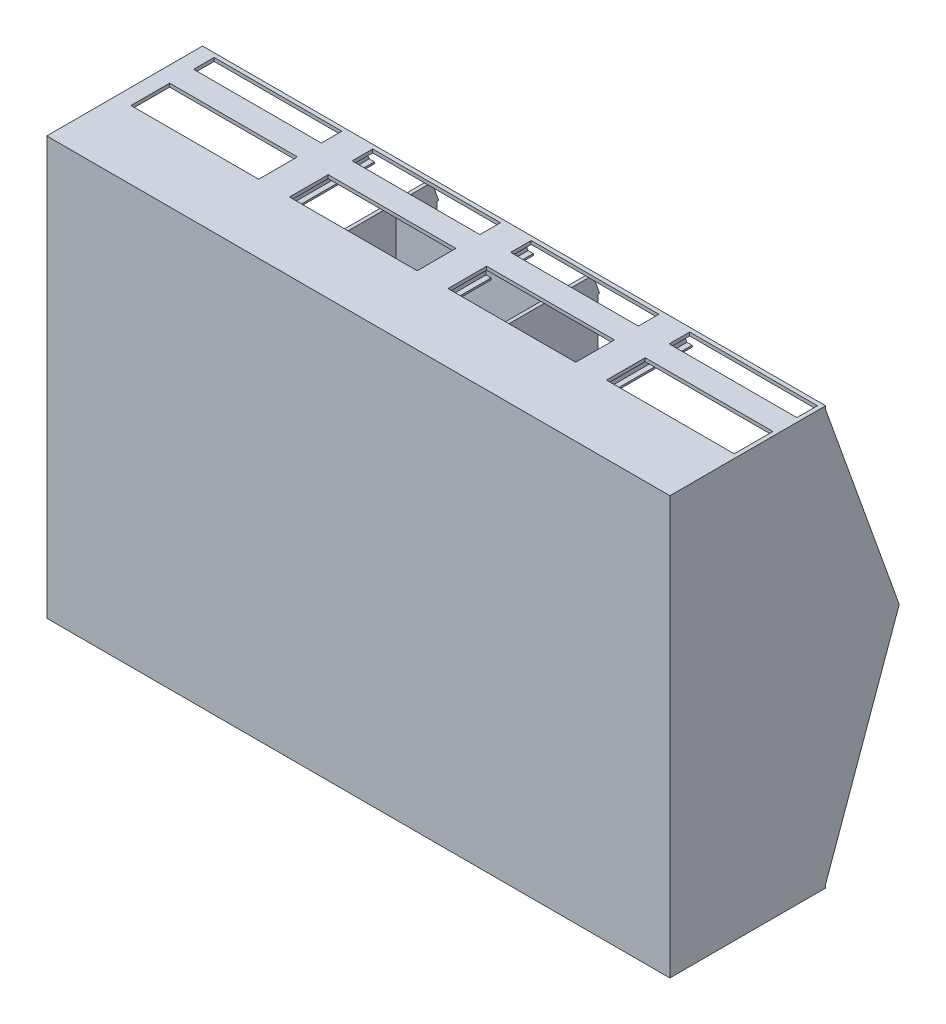
SolidWorks part; units mm, degrees
ref_plane "正面" through (0, 0, 0) normal (0, 0, 1) x (1, 0, 0)
ref_plane "平面" through (0, 0, 0) normal (0, 1, 0) x (1, 0, 0)
ref_plane "右側面" through (0, 0, 0) normal (1, 0, 0) x (0, 0, -1)
sketch "ｽｹｯﾁ1" plane through (0, 0, 0) normal (0, 0, 1) x (1, 0, 0)
  line L1 (-67.545, 11958.8232) -> (18032.455, 11958.8232)
  line L2 (-67.545, 11958.8232) -> (-67.545, -41.1768)
  line L3 (-67.545, -41.1768) -> (18032.455, -41.1768)
  line L4 (18032.455, 11958.8232) -> (18032.455, -41.1768)
  dimension "D1" = 18100
  dimension "D2" = 12000
extrude "ﾎﾞｽ - 押し出し1" add sketch "ｽｹｯﾁ1" along normal blind 1000
sketch "ｽｹｯﾁ11" plane through (18032.455, 0, 0) normal (1, 0, 0) x (0, 0, -1)
  line L1 (-1000, 11958.8232) -> (5700, 11958.8232)
  line L2 (-1000, 11958.8232) -> (-1000, -41.1768)
  line L3 (-1000, -41.1768) -> (5700, -41.1768)
  line L4 (5700, 11958.8232) -> (5700, -41.1768)
  dimension "D1" = 12000
  dimension "D2" = 6700
extrude "ﾎﾞｽ - 押し出し7" add sketch "ｽｹｯﾁ11" along normal blind 100
sketch "ｽｹｯﾁ12" plane through (0, -41.1768, 0) normal (0, -1, 0) x (-1, 0, 0)
  line L0 (67.545, -1000) -> (67.545, 0) construction
  line L1 (-18132.455, -1000) -> (67.545, -1000)
  line L2 (-18132.455, -1000) -> (-18132.455, 3550)
  line L3 (-18132.455, 3550) -> (67.545, 3550)
  line L4 (67.545, -1000) -> (67.545, 3550)
  dimension "D1" = 4550
extrude "ﾎﾞｽ - 押し出し8" add sketch "ｽｹｯﾁ12" along normal blind 100
sketch "ｽｹｯﾁ13" plane through (0, 11958.8232, 0) normal (0, 1, 0) x (1, 0, 0)
  line L1 (18132.455, -1000) -> (-67.545, -1000)
  line L2 (18132.455, -1000) -> (18132.455, 3550)
  line L3 (18132.455, 3550) -> (-67.545, 3550)
  line L4 (-67.545, -1000) -> (-67.545, 3550)
  line L5 (-67.545, 0) -> (-67.545, 3550) construction
  dimension "D1" = 0
  dimension "D2" = 4550
extrude "ﾎﾞｽ - 押し出し9" add sketch "ｽｹｯﾁ13" along normal blind 100
sketch "ｽｹｯﾁ14" plane through (0, 0, 0) normal (0, 0, -1) x (-1, 0, 0)
  line L0 (67.545, -41.1768) -> (-18032.455, -41.1768) construction
  line L1 (-6532.455, -41.1768) -> (-6632.455, -41.1768)
  line L2 (-6532.455, -41.1768) -> (-6532.455, 11958.8232)
  line L3 (-6532.455, 11958.8232) -> (-6632.455, 11958.8232)
  line L4 (-6632.455, -41.1768) -> (-6632.455, 11958.8232)
  line L5 (-18032.455, 11958.8232) -> (67.545, 11958.8232) construction
  line L6 (67.545, -41.1768) -> (-18032.455, -41.1768) construction
  line L7 (-11232.455, -41.1768) -> (-11332.455, -41.1768)
  line L8 (-11232.455, -41.1768) -> (-11232.455, 11958.8232)
  line L9 (-11232.455, 11958.8232) -> (-11332.455, 11958.8232)
  line L10 (-11332.455, -41.1768) -> (-11332.455, 11958.8232)
  line L11 (-18032.455, 11958.8232) -> (67.545, 11958.8232) construction
  line L12 (67.545, 11958.8232) -> (67.545, -41.1768) construction
  dimension "D1" = 100
  dimension "D2" = 100
  dimension "D3" = 4600
  dimension "D4" = 6600
extrude "ﾎﾞｽ - 押し出し10" add sketch "ｽｹｯﾁ14" along normal blind 5700
sketch "ｽｹｯﾁ16" plane through (0, 0, 0) normal (0, 0, -1) x (-1, 0, 0)
  line L0 (67.545, -41.1768) -> (-6532.455, -41.1768) construction
  line L1 (-4622.455, -41.1768) -> (-4522.455, -41.1768)
  line L2 (-4622.455, -41.1768) -> (-4622.455, 458.8232)
  line L3 (-4522.455, 458.8232) -> (-4372.455, 458.8232)
  line L4 (-4522.455, -41.1768) -> (-4522.455, 458.8232)
  line L5 (-6632.455, -41.1768) -> (-11232.455, -41.1768) construction
  line L6 (-4772.455, 508.8232) -> (-4372.455, 508.8232)
  line L7 (-4772.455, 508.8232) -> (-4772.455, 458.8232)
  line L8 (-4772.455, 458.8232) -> (-4622.455, 458.8232)
  line L9 (-4372.455, 508.8232) -> (-4372.455, 458.8232)
  line L10 (-9262.455, -41.1768) -> (-9162.455, -41.1768)
  line L11 (-9262.455, -41.1768) -> (-9262.455, 458.8232)
  line L12 (-9162.455, 458.8232) -> (-9012.455, 458.8232)
  line L13 (-9162.455, -41.1768) -> (-9162.455, 458.8232)
  line L14 (-11332.455, -41.1768) -> (-18032.455, -41.1768) construction
  line L15 (-9412.455, 508.8232) -> (-9012.455, 508.8232)
  line L16 (-9412.455, 508.8232) -> (-9412.455, 458.8232)
  line L17 (-9412.455, 458.8232) -> (-9262.455, 458.8232)
  line L18 (-9012.455, 508.8232) -> (-9012.455, 458.8232)
  line L19 (-13902.455, -41.1768) -> (-13802.455, -41.1768)
  line L20 (-13902.455, -41.1768) -> (-13902.455, 458.8232)
  line L21 (-13802.455, 458.8232) -> (-13652.455, 458.8232)
  line L22 (-13802.455, -41.1768) -> (-13802.455, 458.8232)
  line L23 (-18032.455, 11958.8232) -> (-11332.455, 11958.8232) construction
  line L24 (-14052.455, 508.8232) -> (-13652.455, 508.8232)
  line L25 (-14052.455, 508.8232) -> (-14052.455, 458.8232)
  line L26 (-14052.455, 458.8232) -> (-13902.455, 458.8232)
  line L27 (-13652.455, 508.8232) -> (-13652.455, 458.8232)
  line L28 (-13902.455, 11958.8232) -> (-13802.455, 11958.8232)
  line L29 (-13902.455, 11958.8232) -> (-13902.455, 11458.8232)
  line L30 (-13802.455, 11458.8232) -> (-13652.455, 11458.8232)
  line L31 (-13802.455, 11958.8232) -> (-13802.455, 11458.8232)
  line L32 (-11232.455, 11958.8232) -> (-6632.455, 11958.8232) construction
  line L33 (-14052.455, 11458.8232) -> (-13902.455, 11458.8232)
  line L34 (-14052.455, 11458.8232) -> (-14052.455, 11408.8232)
  line L35 (-14052.455, 11408.8232) -> (-13652.455, 11408.8232)
  line L36 (-13652.455, 11458.8232) -> (-13652.455, 11408.8232)
  line L37 (-9262.455, 11958.8232) -> (-9162.455, 11958.8232)
  line L38 (-9262.455, 11958.8232) -> (-9262.455, 11458.8232)
  line L39 (-9162.455, 11458.8232) -> (-9012.455, 11458.8232)
  line L40 (-9162.455, 11958.8232) -> (-9162.455, 11458.8232)
  line L41 (-6532.455, 11958.8232) -> (67.545, 11958.8232) construction
  line L42 (-9412.455, 11408.8232) -> (-9012.455, 11408.8232)
  line L43 (-9412.455, 11408.8232) -> (-9412.455, 11458.8232)
  line L44 (-9412.455, 11458.8232) -> (-9262.455, 11458.8232)
  line L45 (-9012.455, 11408.8232) -> (-9012.455, 11458.8232)
  line L46 (-4622.455, 11958.8232) -> (-4522.455, 11958.8232)
  line L47 (-4622.455, 11958.8232) -> (-4622.455, 11458.8232)
  line L48 (-4522.455, 11458.8232) -> (-4372.455, 11458.8232)
  line L49 (-4522.455, 11958.8232) -> (-4522.455, 11458.8232)
  line L50 (-13852.455, 13375.4097) -> (-13852.455, -2224.1741) construction
  line L51 (-4772.455, 11408.8232) -> (-4372.455, 11408.8232)
  line L52 (-4772.455, 11408.8232) -> (-4772.455, 11458.8232)
  line L53 (-4772.455, 11458.8232) -> (-4622.455, 11458.8232)
  line L54 (-4372.455, 11408.8232) -> (-4372.455, 11458.8232)
  line L55 (-9212.455, 16545.7899) -> (-9212.455, -4246.1418) construction
  line L56 (-4572.455, 15782.7832) -> (-4572.455, -2796.4291) construction
  line L57 (67.545, 11958.8232) -> (67.545, -41.1768) construction
  dimension "D1" = 400
  dimension "D2" = 150
  dimension "D3" = 100
  dimension "D4" = 50
  dimension "D5" = 500
  dimension "D6" = 400
  dimension "D7" = 50
  dimension "D8" = 150
  dimension "D9" = 100
  dimension "D10" = 500
  dimension "D11" = 50
  dimension "D12" = 100
  dimension "D13" = 400
  dimension "D14" = 150
  dimension "D15" = 500
  dimension "D16" = 400
  dimension "D17" = 150
  dimension "D18" = 100
  dimension "D19" = 50
  dimension "D20" = 500
  dimension "D21" = 500
  dimension "D22" = 50
  dimension "D23" = 400
  dimension "D24" = 100
  dimension "D25" = 150
  dimension "D26" = 400
  dimension "D27" = 50
  dimension "D28" = 500
  dimension "D29" = 150
  dimension "D30" = 100
  dimension "D31" = 50
  dimension "D32" = 50
  dimension "D33" = 50
  dimension "D34" = 50
  dimension "D35" = 50
  dimension "D36" = 50
  dimension "D37" = 4640
  dimension "D38" = 4640
  dimension "D39" = 4640
extrude "ﾎﾞｽ - 押し出し11" add sketch "ｽｹｯﾁ16" along normal blind 5000
sketch "ｽｹｯﾁ15" plane through (18132.455, 0, 0) normal (1, 0, 0) x (0, 0, -1)
  line L0 (5700, 11958.8232) -> (3550, 11958.8232)
  line L1 (3550, 11958.8232) -> (5700, 5958.8232)
  line L2 (5700, -41.1768) -> (5700, 11958.8232) construction
  line L3 (5700, 5958.8232) -> (3550, -41.1768)
  line L4 (3550, -41.1768) -> (5700, -41.1768)
  line L5 (5700, -41.1768) -> (5700, 11958.8232)
  line L6 (-1000, 12058.8232) -> (-1000, -141.1768) construction
  line M4 (3550, -41.1768) -> (5700, -41.1768)
  line M5 (5700, -41.1768) -> (5700, 11958.8232)
  line M6 (5700, 11958.8232) -> (3550, 11958.8232)
  dimension "D1" = 4550
  dimension "D2" = 6000
extrude "ｶｯﾄ - 押し出し7" cut sketch "ｽｹｯﾁ15" against normal through all contours L3 M5 M4 | L1 M6 M5
sketch "ｽｹｯﾁ17" plane through (6532.455, 0, 0) normal (-1, 0, 0) x (0, 0, 1)
  line L0 (0, -41.1768) -> (0, 11958.8232) construction
  line L1 (0, 3878.8232) -> (-2000, 3878.8232)
  line L2 (0, 3878.8232) -> (0, 5758.8232)
  line L3 (0, 5758.8232) -> (-2000, 5758.8232)
  line L4 (-2000, 3878.8232) -> (-2000, 5758.8232)
  dimension "D1" = 1880
  dimension "D2" = 2000
  dimension "D3" = 200
extrude "ｶｯﾄ - 押し出し8" cut sketch "ｽｹｯﾁ17" against normal blind 100
sketch "ｽｹｯﾁ18" plane through (11232.455, 0, 0) normal (-1, 0, 0) x (0, 0, 1)
  line L0 (0, -41.1768) -> (0, 11958.8232) construction
  line L1 (0, 2948.8232) -> (-2000, 2948.8232)
  line L2 (0, 2948.8232) -> (0, 4828.8232)
  line L3 (0, 4828.8232) -> (-2000, 4828.8232)
  line L4 (-2000, 2948.8232) -> (-2000, 4828.8232)
  dimension "D1" = 1880
  dimension "D2" = 2000
  dimension "D3" = 1130
extrude "ｶｯﾄ - 押し出し9" cut sketch "ｽｹｯﾁ18" against normal blind 100
sketch "ｽｹｯﾁ19" plane through (0, 12058.8232, 0) normal (0, 1, 0) x (1, 0, 0)
  line L0 (-67.545, -1000) -> (18132.455, -1000) construction
  line L1 (392.455, 2130) -> (4122.455, 2130)
  line L2 (392.455, 2130) -> (392.455, 1000)
  line L3 (392.455, 1000) -> (4122.455, 1000)
  line L4 (4122.455, 2130) -> (4122.455, 1000)
  line L5 (392.455, 3430) -> (4122.455, 3430)
  line L6 (392.455, 3430) -> (392.455, 2830)
  line L7 (392.455, 2830) -> (4122.455, 2830)
  line L8 (4122.455, 3430) -> (4122.455, 2830)
  line L10 (4522.455, 3550) -> (4522.455, 0) construction
  line L11 (5022.455, 2130) -> (8752.455, 2130)
  line L12 (5022.455, 1000) -> (8752.455, 1000)
  line L13 (5022.455, 2130) -> (5022.455, 1000)
  line L14 (5022.455, 2830) -> (8752.455, 2830)
  line L15 (5022.455, 3430) -> (5022.455, 2830)
  line L16 (5022.455, 3430) -> (8752.455, 3430)
  line L17 (8752.455, 2130) -> (8752.455, 1000)
  line L18 (8752.455, 3430) -> (8752.455, 2830)
  line L19 (9652.455, 2130) -> (13382.455, 2130)
  line L20 (9652.455, 1000) -> (13382.455, 1000)
  line L21 (9652.455, 2130) -> (9652.455, 1000)
  line L22 (9652.455, 2830) -> (13382.455, 2830)
  line L23 (9652.455, 3430) -> (9652.455, 2830)
  line L24 (9652.455, 3430) -> (13382.455, 3430)
  line L25 (13382.455, 2130) -> (13382.455, 1000)
  line L26 (13382.455, 3430) -> (13382.455, 2830)
  line L27 (14282.455, 2130) -> (18012.455, 2130)
  line L28 (14282.455, 1000) -> (18012.455, 1000)
  line L29 (14282.455, 2130) -> (14282.455, 1000)
  line L30 (14282.455, 2830) -> (18012.455, 2830)
  line L31 (14282.455, 3430) -> (14282.455, 2830)
  line L32 (14282.455, 3430) -> (18012.455, 3430)
  line L33 (18012.455, 2130) -> (18012.455, 1000)
  line L34 (18012.455, 3430) -> (18012.455, 2830)
  line L35 (392.455, 2130) -> (5022.455, 2130) construction
  line L36 (4622.455, 3550) -> (4622.455, 0) construction
  dimension "D1" = 3730
  dimension "D2" = 3730
  dimension "D3" = 700
  dimension "D4" = 600
  dimension "D5" = 1130
  dimension "D6" = 2000
  dimension "D7" = 400
  dimension "D8" = 400
  dimension "D9" = 4
  dimension "D10" = 4630
  dimension "D11" = 400
extrude "ｶｯﾄ - 押し出し10" cut sketch "ｽｹｯﾁ19" against normal blind 100
sketch "ｽｹｯﾁ20" plane through (0, -141.1768, 0) normal (0, -1, 0) x (-1, 0, 0)
  line L1 (-2197.455, 2130) -> (-332.455, 2130)
  line L2 (-2197.455, 2130) -> (-2197.455, 1000)
  line L3 (-2197.455, 1000) -> (-332.455, 1000)
  line L4 (-332.455, 2130) -> (-332.455, 1000)
  line L5 (-2197.455, 3430) -> (-332.455, 3430)
  line L6 (-2197.455, 3430) -> (-2197.455, 2830)
  line L7 (-2197.455, 2830) -> (-332.455, 2830)
  line L8 (-332.455, 3430) -> (-332.455, 2830)
  line L9 (67.545, -1000) -> (67.545, 3550) construction
  line L10 (-18132.455, -1000) -> (67.545, -1000) construction
  line L11 (-4622.455, 3729.1667) -> (-4622.455, 0) construction
  line L12 (-5022.455, 1000) -> (-8752.455, 1000)
  line L13 (-5022.455, 1000) -> (-5022.455, 2130)
  line L14 (-5022.455, 2130) -> (-8752.455, 2130)
  line L15 (-8752.455, 1000) -> (-8752.455, 2130)
  line L16 (-5022.455, 2830) -> (-8752.455, 2830)
  line L17 (-5022.455, 2830) -> (-5022.455, 3430)
  line L18 (-5022.455, 3430) -> (-8752.455, 3430)
  line L19 (-8752.455, 2830) -> (-8752.455, 3430)
  line L20 (-13802.455, 3729.1667) -> (-13802.455, 3550) construction
  line L21 (-13402.455, 2130) -> (-11537.455, 2130)
  line L22 (-13402.455, 2130) -> (-13402.455, 1000)
  line L23 (-13402.455, 1000) -> (-11537.455, 1000)
  line L24 (-11537.455, 2130) -> (-11537.455, 1000)
  line L25 (-13402.455, 3430) -> (-11537.455, 3430)
  line L26 (-13402.455, 3430) -> (-13402.455, 2830)
  line L27 (-13402.455, 2830) -> (-11537.455, 2830)
  line L28 (-11537.455, 3430) -> (-11537.455, 2830)
  dimension "D1" = 1865
  dimension "D2" = 1865
  dimension "D3" = 700
  dimension "D4" = 600
  dimension "D5" = 1130
  dimension "D6" = 400
  dimension "D7" = 400
  dimension "D8" = 2000
  dimension "D9" = 3730
  dimension "D10" = 3730
  dimension "D11" = 700
  dimension "D12" = 600
  dimension "D13" = 1130
  dimension "D14" = 400
  dimension "D15" = 400
  dimension "D16" = 2000
  dimension "D17" = 600
  dimension "D18" = 1130
  dimension "D19" = 700
  dimension "D20" = 2000
  dimension "D21" = 400
  dimension "D22" = 400
  dimension "D23" = 1865
  dimension "D24" = 1865
extrude "ｶｯﾄ - 押し出し11" cut sketch "ｽｹｯﾁ20" against normal blind 100
sketch "ｽｹｯﾁ21" plane through (11232.455, 0, 0) normal (-1, 0, 0) x (0, 0, 1)
  line L0 (-5700, 5958.8232) -> (-2500, 5958.8232)
  line L1 (-2500, 5958.8232) -> (-2500, 11958.8232)
  line L2 (-2830, 11958.8232) -> (-2130, 11958.8232) construction
  line L3 (0, 4828.8232) -> (0, 11958.8232) construction
  line L4 (-5700, 5958.8232) -> (-5664.1667, 6058.8232)
  line L5 (-3550, 11958.8232) -> (-5700, 5958.8232) construction
  line L6 (-5664.1667, 6058.8232) -> (-2600, 6058.8232)
  line L7 (-2600, 6058.8232) -> (-2600, 11958.8232)
  line L8 (-3550, 11958.8232) -> (0, 11958.8232) construction
  line L9 (-2600, 11958.8232) -> (-2500, 11958.8232)
  dimension "D1" = 2500
  dimension "D2" = 100
  dimension "D3" = 100
extrude "ﾎﾞｽ - 押し出し12" add sketch "ｽｹｯﾁ21" along normal up to next
sketch "ｽｹｯﾁ22" plane through (6532.455, 0, 0) normal (-1, 0, 0) x (0, 0, 1)
  line L0 (-5664.1667, 6058.8232) -> (-3700, 6058.8232)
  line L1 (-3550, 11958.8232) -> (-5700, 5958.8232) construction
  line L2 (-3700, 8458.8232) -> (-3700, 6058.8232)
  line L3 (-3700, 8458.8232) -> (-2700, 8458.8232)
  line L4 (-2700, 8458.8232) -> (-2700, 9258.8232)
  line L5 (-2700, 9258.8232) -> (-3700, 9258.8232)
  line L6 (-3700, 9258.8232) -> (-3700, 11408.8232)
  line L7 (-3747.0833, 11408.8232) -> (0, 11408.8232) construction
  line L8 (-3700, 11408.8232) -> (-3747.0833, 11408.8232)
  line L9 (-3747.0833, 11408.8232) -> (-5664.1667, 6058.8232)
  dimension "D1" = 100
  dimension "D2" = 1000
  dimension "D3" = 2000
  dimension "D4" = 1000
  dimension "D5" = 800
  dimension "D6" = 2400
extrude "ｶｯﾄ - 押し出し13" cut sketch "ｽｹｯﾁ22" against normal up to surface (4800 mm away) up to face at (11332.455, 7168.054, -2014.6154)
